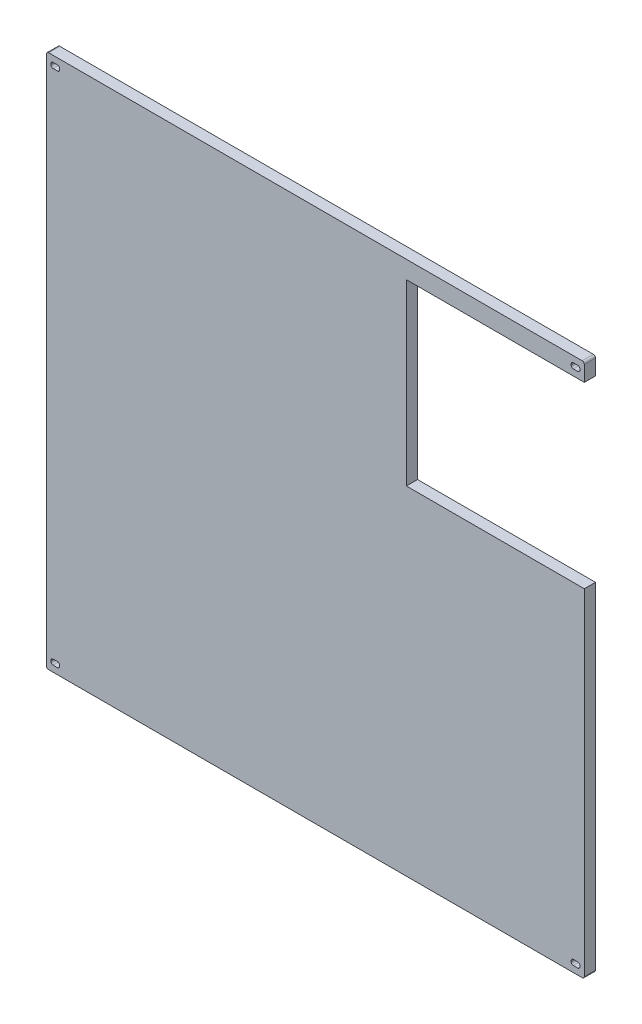
SolidWorks part; units mm, degrees
ref_plane "Front Plane" through (0, 0, 0) normal (0, 0, 1) x (1, 0, 0)
ref_plane "Top Plane" through (0, 0, 0) normal (0, 1, 0) x (1, 0, 0)
ref_plane "Right Plane" through (0, 0, 0) normal (1, 0, 0) x (0, 0, -1)
sketch "Sketch1" plane through (0, 0, 0) normal (0, 0, 1) x (1, 0, 0)
  line L0 (-5, 10.5) -> (-5, 9.5)
  line L1 (0, 0) -> (-611.632, 0)
  line L2 (0, 0) -> (0, 384.2809)
  line L3 (0, 607.568) -> (-611.632, 607.568)
  line L4 (-611.632, 0) -> (-611.632, 607.568)
  line L5 (0, 587.4809) -> (0, 607.568)
  line L6 (0, 587.4809) -> (-202.3951, 587.4809)
  line L8 (0, 384.2809) -> (-202.3951, 384.2809)
  line L9 (-202.3951, 587.4809) -> (-202.3951, 384.2809)
  line L10 (-7.5, 13) -> (-12.5, 13)
  line L11 (-15, 10.5) -> (-15, 9.5)
  line L12 (-7.5, 7) -> (-12.5, 7)
  line L13 (-10, 13) -> (-10, 7) construction
  line L14 (-15, 10) -> (-5, 10) construction
  line L15 (-596.63, 10.5) -> (-596.63, 9.5)
  line L16 (-599.13, 7) -> (-604.13, 7)
  line L17 (-606.63, 10.5) -> (-606.63, 9.5)
  line L18 (-599.13, 13) -> (-604.13, 13)
  line L19 (-596.63, 598.07) -> (-596.63, 597.07)
  line L20 (-599.13, 594.57) -> (-604.13, 594.57)
  line L21 (-606.63, 598.07) -> (-606.63, 597.07)
  line L22 (-599.13, 600.57) -> (-604.13, 600.57)
  line L23 (-5, 598.07) -> (-5, 597.07)
  line L24 (-7.5, 594.57) -> (-12.5, 594.57)
  line L25 (-15, 598.07) -> (-15, 597.07)
  line L26 (-7.5, 600.57) -> (-12.5, 600.57)
  arc A0 (-5, 10.5) -> (-7.5, 13) centre (-7.5, 10.5) ccw
  arc A1 (-12.5, 13) -> (-15, 10.5) centre (-12.5, 10.5) ccw
  arc A2 (-5, 9.5) -> (-7.5, 7) centre (-7.5, 9.5) cw
  arc A3 (-15, 9.5) -> (-12.5, 7) centre (-12.5, 9.5) ccw
  arc A4 (-596.63, 9.5) -> (-599.13, 7) centre (-599.13, 9.5) cw
  arc A5 (-606.63, 9.5) -> (-604.13, 7) centre (-604.13, 9.5) ccw
  arc A6 (-604.13, 13) -> (-606.63, 10.5) centre (-604.13, 10.5) ccw
  arc A7 (-596.63, 10.5) -> (-599.13, 13) centre (-599.13, 10.5) ccw
  arc A8 (-596.63, 597.07) -> (-599.13, 594.57) centre (-599.13, 597.07) cw
  arc A9 (-606.63, 597.07) -> (-604.13, 594.57) centre (-604.13, 597.07) ccw
  arc A10 (-604.13, 600.57) -> (-606.63, 598.07) centre (-604.13, 598.07) ccw
  arc A11 (-596.63, 598.07) -> (-599.13, 600.57) centre (-599.13, 598.07) ccw
  arc A12 (-5, 597.07) -> (-7.5, 594.57) centre (-7.5, 597.07) cw
  arc A13 (-15, 597.07) -> (-12.5, 594.57) centre (-12.5, 597.07) ccw
  arc A14 (-12.5, 600.57) -> (-15, 598.07) centre (-12.5, 598.07) ccw
  arc A15 (-5, 598.07) -> (-7.5, 600.57) centre (-7.5, 598.07) ccw
  point P21 (-5, 10)
  dimension "D4" = 2.5
  dimension "D1" = 611.632
  dimension "D2" = 607.568
  dimension "D3" = 6
  dimension "D5" = 10
  dimension "D6" = 10
  dimension "D7" = 2
  dimension "D8" = 2
  dimension "1000" = 10
  dimension "D9" = 5
  dimension "D10" = 6.998
  dimension "D11" = 5.002
  dimension "D12" = 384.2809
  dimension "D13" = 203.2
  dimension "D14" = 202.3951
extrude "Boss-Extrude2" add sketch "Sketch1" along normal blind 12.7
fillet "Fillet2" radius 2.5 4 edges at (-611.632, 0, 6.35) (0, 0, 6.35) (-611.632, 607.568, 6.35) (0, 607.568, 6.35)
